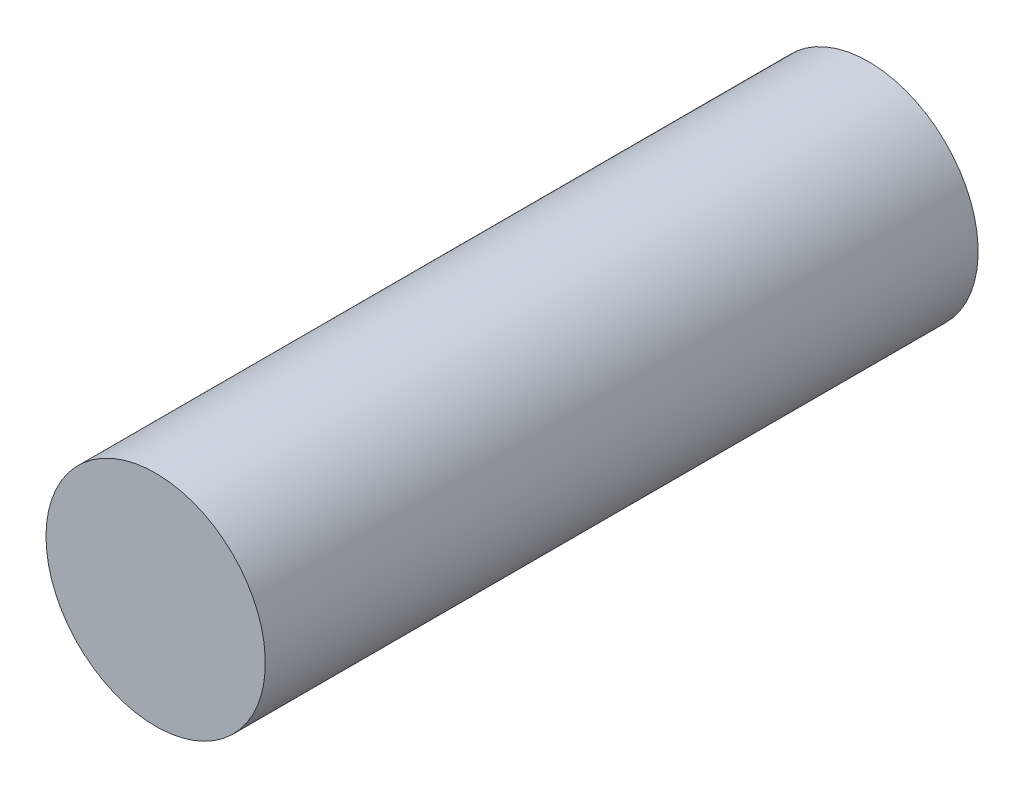
SolidWorks part; units mm, degrees
ref_plane "Front Plane" through (0, 0, 0) normal (0, 0, 1) x (1, 0, 0)
ref_plane "Top Plane" through (0, 0, 0) normal (0, 1, 0) x (1, 0, 0)
ref_plane "Right Plane" through (0, 0, 0) normal (1, 0, 0) x (0, 0, -1)
sketch "Sketch1" plane through (0, 0, 0) normal (0, 0, 1) x (1, 0, 0)
  circle A0 centre (0, 0) radius 8
extrude "Boss-Extrude1" add sketch "Sketch1" along normal blind 52
cosmetic thread "Cosmetic Thread1" parameters "D1"=22, "D2"=14.344
cosmetic thread "Cosmetic Thread2" parameters "D1"=15, "D2"=14.344
